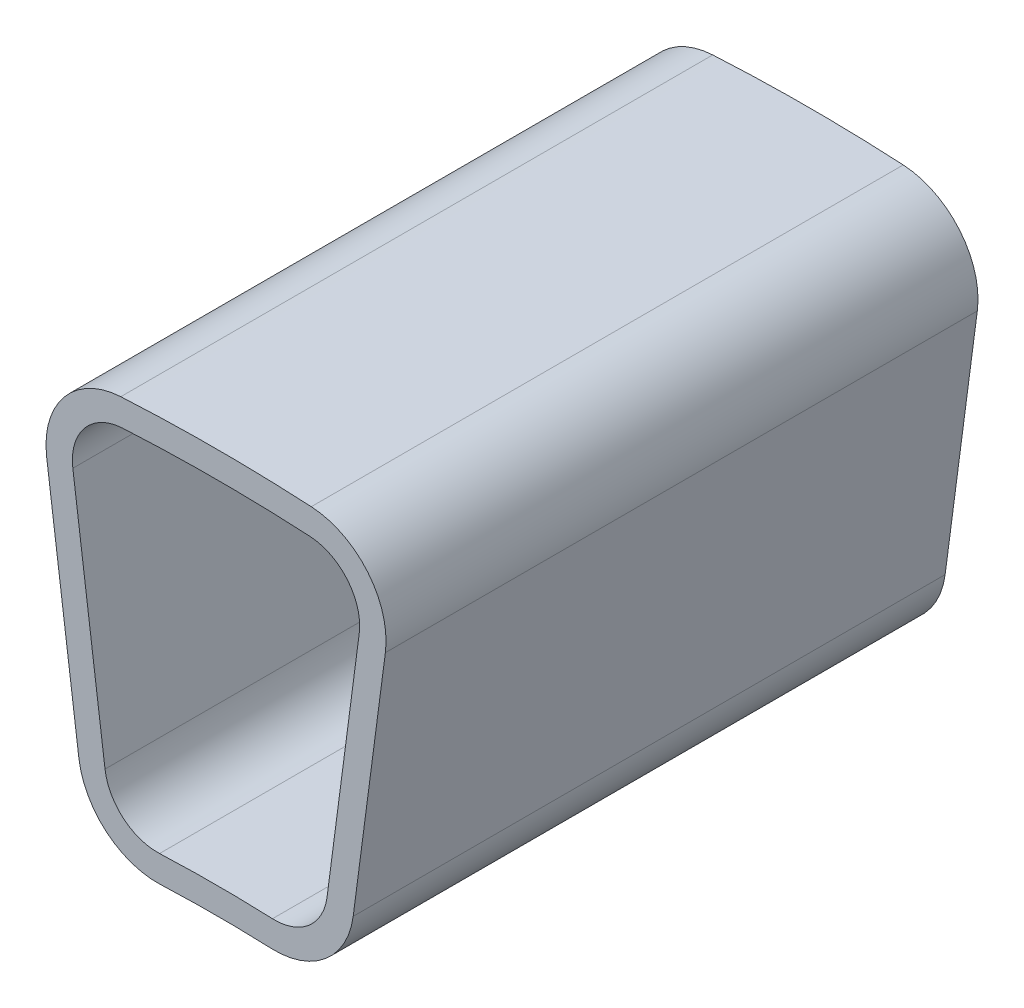
SolidWorks part; units mm, degrees
material "Copper"
ref_plane "Front Plane" through (0, 0, 0) normal (0, 0, 1) x (1, 0, 0)
ref_plane "Top Plane" through (0, 0, 0) normal (0, 1, 0) x (1, 0, 0)
ref_plane "Right Plane" through (0, 0, 0) normal (1, 0, 0) x (0, 0, -1)
sketch "Sketch1" plane through (0, 0, 0) normal (0, 0, 1) x (1, 0, 0)
  line L0 (7.7973, 78.3796) -> (9.6268, 92.2757)
  line L1 (-9.6268, 92.2757) -> (-7.7973, 78.3796)
  line L2 (-8.1396, 92.4715) -> (-6.3101, 78.5753)
  line L3 (6.3101, 78.5753) -> (8.1396, 92.4715)
  line L4 (-8.1396, 92.4715) -> (-6.3101, 78.5753)
  line L5 (6.3101, 78.5753) -> (8.1396, 92.4715)
  arc A0 (9.6268, 92.2757) -> (5.4152, 97.3561) centre (5.1652, 92.863) ccw
  arc A1 (5.4152, 97.3561) -> (-5.4152, 97.3561) centre (0, 0) ccw
  arc A2 (-5.4152, 97.3561) -> (-9.6268, 92.2757) centre (-5.1652, 92.863) ccw
  arc A3 (-7.7973, 78.3796) -> (-3.1459, 74.4709) centre (-3.3358, 78.9669) ccw
  arc A4 (3.1459, 74.4709) -> (-3.1459, 74.4709) centre (0, 0) ccw
  arc A5 (3.1459, 74.4709) -> (7.7973, 78.3796) centre (3.3358, 78.9669) ccw
  arc A6 (8.1396, 92.4715) -> (5.3319, 95.8584) centre (5.1652, 92.863) ccw
  arc A7 (5.3319, 95.8584) -> (-5.3319, 95.8584) centre (0, 0) ccw
  arc A8 (-5.3319, 95.8584) -> (-8.1396, 92.4715) centre (-5.1652, 92.863) ccw
  arc A9 (-6.3101, 78.5753) -> (-3.2092, 75.9696) centre (-3.3358, 78.9669) ccw
  arc A10 (3.2092, 75.9696) -> (-3.2092, 75.9696) centre (0, 0) ccw
  arc A11 (3.2092, 75.9696) -> (6.3101, 78.5753) centre (3.3358, 78.9669) ccw
  arc A12 (8.1396, 92.4715) -> (5.3319, 95.8584) centre (5.1652, 92.863) ccw
  arc A13 (5.3319, 95.8584) -> (-5.3319, 95.8584) centre (0, 0) ccw
  arc A14 (-5.3319, 95.8584) -> (-8.1396, 92.4715) centre (-5.1652, 92.863) ccw
  arc A15 (-6.3101, 78.5753) -> (-3.2092, 75.9696) centre (-3.3358, 78.9669) ccw
  arc A16 (3.2092, 75.9696) -> (-3.2092, 75.9696) centre (0, 0) ccw
  arc A17 (3.2092, 75.9696) -> (6.3101, 78.5753) centre (3.3358, 78.9669) ccw
  dimension "D1" = 0
  dimension "D2" = 1.5
extrude "Boss-Extrude1" add sketch "Sketch1" along normal up to surface (33.65 mm away)
